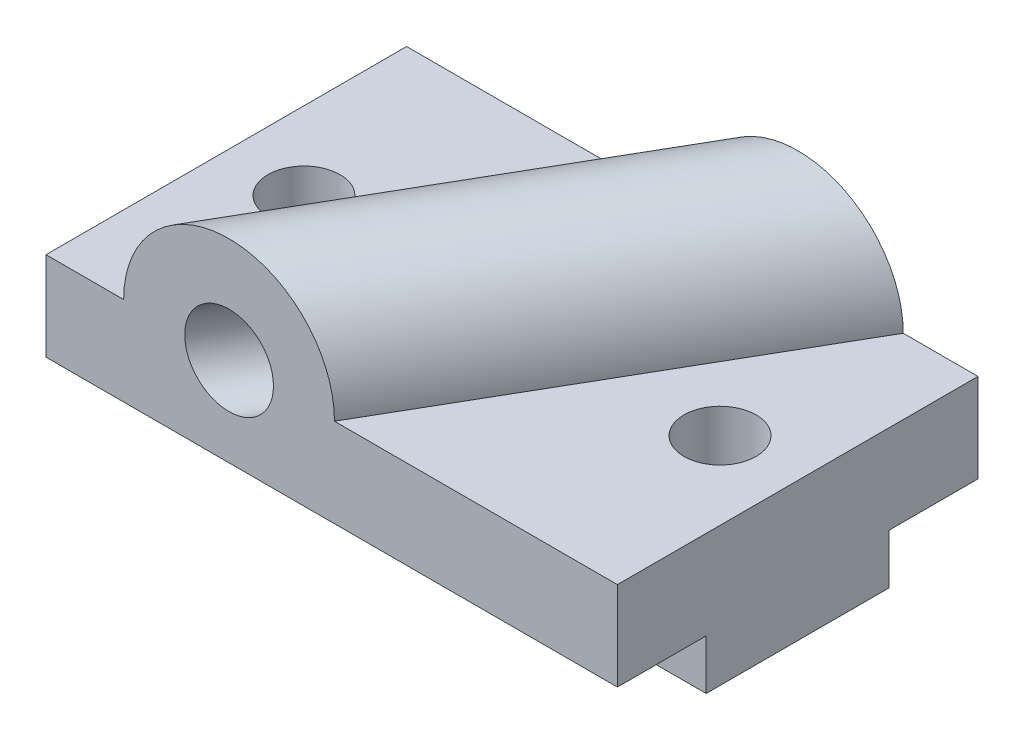
SolidWorks part; units mm, degrees
ref_plane "Front Plane" through (0, 0, 0) normal (0, 0, 1) x (1, 0, 0)
ref_plane "Top Plane" through (0, 0, 0) normal (0, 1, 0) x (1, 0, 0)
ref_plane "Right Plane" through (0, 0, 0) normal (1, 0, 0) x (0, 0, -1)
sketch "Sketch1" plane through (0, 0, 0) normal (1, 0, 0) x (0, 0, -1)
  line L0 (32.5, 0) -> (-32.5, 0)
  line L1 (-32.5, 0) -> (-32.5, -16)
  line L2 (-32.5, -16) -> (-16.5, -16)
  line L3 (-16.5, -16) -> (-16.5, -25)
  line L4 (-16.5, -25) -> (16.5, -25)
  line L6 (16.5, -16) -> (16.5, -25)
  line L7 (32.5, -16) -> (16.5, -16)
  line L8 (32.5, 0) -> (32.5, -16)
  dimension "D1" = 65
  dimension "D2" = 33
  dimension "D3" = 25
  dimension "D4" = 9
  dimension "D5" = 16
extrude "Boss-Extrude1" add sketch "Sketch1" along normal mid plane 103
sketch "Sketch2" plane through (0, 0, 0) normal (0, 1, 0) x (1, 0, 0)
  line L0 (-51.5, 32.5) -> (-51.5, -32.5) construction
  circle A0 centre (-37.5, 0) radius 6.5
  point P2 (0, 0)
  dimension "D1" = 13
  dimension "D2" = 14
extrude "Cut-Extrude1" cut sketch "Sketch2" against normal through all
mirror "Mirror1" about plane through (0, 0, 0) normal (1, 0, 0) of "Cut-Extrude1"
sketch "Sketch4" plane through (0, 0, 0) normal (0, 1, 0) x (1, 0, 0)
  line L0 (15.4061, -32.5) -> (23.4021, -18.6506)
  line L1 (51.5, -32.5) -> (-51.5, -32.5) construction
  dimension "D1" = 60
sketch "Sketch5" plane through (0, 0, 32.5) normal (0, 0, 1) x (1, 0, 0)
  line L0 (51.5, 0) -> (-51.5, 0) construction
  line L1 (0.5, 0) -> (-37.5, 0)
  line L2 (-51.5, 0) -> (-51.5, -16) construction
  arc A0 (-37.5, 0) -> (0.5, 0) centre (-18.5, 0) cw
  dimension "D1" = 19
  dimension "D2" = 14
extrude "Boss-Extrude4" add sketch "Sketch5" along direction (0.5, 0, -0.866) on the side against the normal up to surface (65 mm away)
sketch "Sketch7" plane through (0, 0, 32.5) normal (0, 0, 1) x (1, 0, 0)
  circle A0 centre (-18.5, 0) radius 8
  dimension "D1" = 16
extrude "Cut-Extrude3" cut sketch "Sketch7" along direction (0.5, 0, -0.866) on the side against the normal up to surface (75.0555 mm away)
